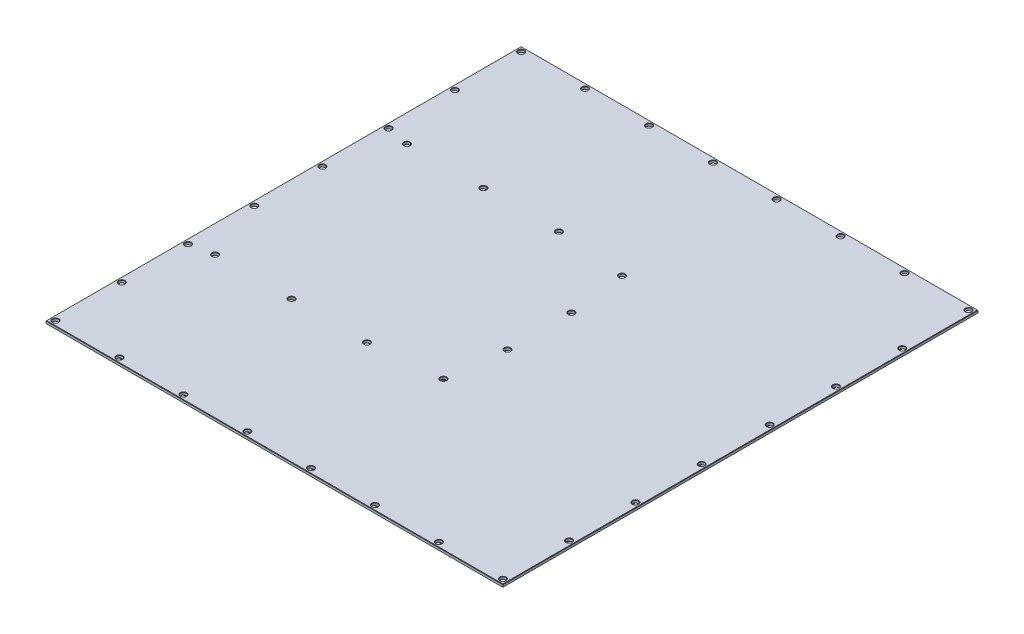
SolidWorks part; units mm, degrees
ref_plane "front" through (0, 0, 0) normal (0, 0, 1) x (1, 0, 0)
ref_plane "top" through (0, 0, 0) normal (0, 1, 0) x (1, 0, 0)
ref_plane "right" through (0, 0, 0) normal (1, 0, 0) x (0, 0, -1)
sketch "Sketch1" plane through (0, 0, 0) normal (0, 1, 0) x (1, 0, 0)
  line L0 (0, 165.1) -> (107.9212, 165.1) construction
  line L1 (0, 330.2) -> (317.5, 330.2)
  line L2 (0, 330.2) -> (0, 0)
  line L3 (0, 0) -> (317.5, 0)
  line L5 (158.75, 0) -> (158.75, 96.4761) construction
  line L6 (317.5, 330.2) -> (317.5, 0)
  circle A0 centre (3.302, 326.898) radius 1.9812
  circle A1 centre (3.302, 141.4526) radius 1.9812
  circle A2 centre (47.752, 326.898) radius 1.9812
  circle A3 centre (92.202, 326.898) radius 1.9812
  circle A4 centre (136.652, 326.898) radius 1.9812
  circle A5 centre (3.302, 280.8478) radius 1.9812
  circle A6 centre (3.302, 234.7976) radius 1.9812
  circle A7 centre (3.302, 188.7474) radius 1.9812
  circle A8 centre (3.302, 95.4024) radius 1.9812
  circle A9 centre (3.302, 49.3522) radius 1.9812
  circle A10 centre (136.652, 3.302) radius 1.9812
  circle A11 centre (92.202, 3.302) radius 1.9812
  circle A12 centre (47.752, 3.302) radius 1.9812
  circle A13 centre (3.302, 3.302) radius 1.9812
  circle A14 centre (314.198, 3.302) radius 1.9812
  circle A15 centre (269.748, 3.302) radius 1.9812
  circle A16 centre (225.298, 3.302) radius 1.9812
  circle A17 centre (180.848, 3.302) radius 1.9812
  circle A18 centre (314.198, 49.3522) radius 1.9812
  circle A19 centre (314.198, 95.4024) radius 1.9812
  circle A20 centre (314.198, 188.7474) radius 1.9812
  circle A21 centre (314.198, 234.7976) radius 1.9812
  circle A22 centre (314.198, 280.8478) radius 1.9812
  circle A23 centre (180.848, 326.898) radius 1.9812
  circle A24 centre (225.298, 326.898) radius 1.9812
  circle A25 centre (269.748, 326.898) radius 1.9812
  circle A26 centre (314.198, 141.4526) radius 1.9812
  circle A27 centre (314.198, 326.898) radius 1.9812
  circle A28 centre (19.05, 231.775) radius 1.9812
  circle A29 centre (72.2122, 231.775) radius 1.9812
  circle A30 centre (124.6378, 231.775) radius 1.9812
  circle A31 centre (177.8, 231.775) radius 1.9812 construction
  circle A32 centre (177.8, 98.425) radius 1.9812 construction
  circle A33 centre (124.6378, 98.425) radius 1.9812
  circle A34 centre (72.2122, 98.425) radius 1.9812
  circle A35 centre (19.05, 98.425) radius 1.9812
  circle A36 centre (177.8, 187.325) radius 1.9812
  circle A37 centre (177.8, 142.875) radius 1.9812
  dimension "D12" = 3.9624
  dimension "D1" = 330.2
  dimension "D2" = 317.5
  dimension "D3" = 44.45
  dimension "D4" = 3.302
  dimension "D5" = 46.0502
  dimension "D6" = 44.196
  dimension "D7" = 47.2948
  dimension "D8" = 3.302
  dimension "D9" = 46.0502
  dimension "D10" = 44.45
  dimension "D11" = 44.45
  dimension "D13" = 19.05
  dimension "D14" = 98.425
  dimension "D15" = 53.1622
  dimension "D16" = 44.45
  dimension "D17" = 177.8
  dimension "D18" = 44.196
  dimension "D19" = 177.8
  dimension "D20" = 52.4256
extrude "Extrude4" add sketch "Sketch1" along normal blind 3.175
sketch "box walls" plane through (0, 0, 0) normal (0, -1, 0) x (1, 0, 0)
  line L0 (0, -165.1) -> (53.4599, -165.1) construction
  line L1 (0, -330.2) -> (0, 0) construction
  line L2 (180.975, -215.9) -> (180.975, -114.3)
  line L3 (295.275, -320.675) -> (22.225, -320.675)
  line L4 (9.525, -307.975) -> (9.525, -247.65)
  line L5 (22.225, -234.95) -> (161.925, -234.95)
  line L6 (307.975, -307.975) -> (307.975, -22.225)
  line L7 (22.225, -95.25) -> (161.925, -95.25)
  line L8 (9.525, -22.225) -> (9.525, -82.55)
  line L9 (295.275, -9.525) -> (22.225, -9.525)
  line L10 (317.5, -330.2) -> (0, -330.2) construction
  line L11 (161.925, -101.6) -> (22.225, -101.6)
  line L12 (174.625, -114.3) -> (174.625, -215.9)
  line L13 (161.925, -228.6) -> (22.225, -228.6)
  line L14 (9.525, -114.3) -> (9.525, -215.9)
  line L15 (317.5, 0) -> (317.5, -330.2) construction
  line L16 (0, 0) -> (317.5, 0) construction
  line L17 (175.3954, -100.8296) -> (170.9053, -105.3197) construction
  line L18 (87.1603, -95.25) -> (87.1603, -101.6) construction
  line L19 (87.1603, -228.6) -> (87.1603, -234.95) construction
  line L20 (180.975, -165.1) -> (174.625, -165.1) construction
  line L21 (0, -330.2) -> (0, 0) construction
  line L22 (0, 0) -> (317.5, 0) construction
  line L23 (0, -330.2) -> (0, 0) construction
  arc A0 (307.975, -307.975) -> (295.275, -320.675) centre (295.275, -307.975) cw
  arc A1 (22.225, -320.675) -> (9.525, -307.975) centre (22.225, -307.975) cw
  arc A2 (9.525, -247.65) -> (22.225, -234.95) centre (22.225, -247.65) cw
  arc A3 (22.225, -228.6) -> (9.525, -215.9) centre (22.225, -215.9) cw
  arc A4 (174.625, -215.9) -> (161.925, -228.6) centre (161.925, -215.9) cw
  arc A5 (161.925, -101.6) -> (174.625, -114.3) centre (161.925, -114.3) cw
  arc A6 (22.225, -101.6) -> (9.525, -114.3) centre (22.225, -114.3) ccw
  arc A7 (161.925, -234.95) -> (180.975, -215.9) centre (161.925, -215.9) ccw
  arc A8 (9.525, -82.55) -> (22.225, -95.25) centre (22.225, -82.55) ccw
  arc A9 (22.225, -9.525) -> (9.525, -22.225) centre (22.225, -22.225) ccw
  arc A10 (307.975, -22.225) -> (295.275, -9.525) centre (295.275, -22.225) ccw
  arc A11 (161.925, -95.25) -> (180.975, -114.3) centre (161.925, -114.3) cw
  circle A12 centre (173.1503, -103.0747) radius 1.9812
  circle A13 centre (173.1503, -227.1253) radius 1.9812
  point P9 (307.975, -165.1)
  point P18 (9.525, -165.1)
  point P43 (180.975, -165.1)
  point P59 (87.1603, -98.425)
  point P60 (87.1603, -231.775)
  point P63 (177.8, -165.1)
  dimension "D1" = 12.7
  dimension "D2" = 19.05
  dimension "D12" = 3.9624
  dimension "D5" = 12.7
  dimension "D13" = 114.3
  dimension "D3" = 6.35
  dimension "3/8 under" = 9.525
  dimension "D4" = 9.525
  dimension "D6" = 139.7
  dimension "D7" = 180.975
  dimension "D8" = 133.35
  dimension "slot width" = 6.35
  dimension "D9" = 177.8
  dimension "D10" = 161.925
  dimension "D11" = 45
  dimension "D14" = 9.525
sketch "Sketch4" plane through (0, 0, 0) normal (0, -1, 0) x (1, 0, 0)
  circle A0 centre (173.1503, -227.1253) radius 1.9812 construction
  circle A1 centre (173.1503, -103.0747) radius 1.9812 construction
  circle A2 centre (173.1503, -227.1253) radius 1.9812
  circle A3 centre (173.1503, -103.0747) radius 1.9812
extrude "new holes" cut sketch "Sketch4" against normal through all
ref_plane "Profile plane" through (9.525, 0, -22.225) normal (0, 0, -1) x (-1, 0, 0)
sketch "groove profile" plane through (9.525, 0, -22.225) normal (0, 0, -1) x (-1, 0, 0)
  line L0 (0.1189, 0) -> (-1.2365, 0)
  line L1 (3.8181, 1.1035) -> (3.8181, 1.397)
  line L2 (9.525, 0) -> (-43.9349, 0) construction
  line L5 (3.8181, 1.397) -> (9.525, 1.397)
  line L6 (0.4145, 1.1035) -> (0.1189, 0)
  line L7 (0.4145, 1.1035) -> (1.8207, 1.1035)
  line L8 (1.8207, 1.1035) -> (2.1163, 0)
  line L9 (2.1163, 0) -> (3.5225, 0)
  line L10 (3.5225, 0) -> (3.8181, 1.1035)
  line L14 (-1.2365, 0) -> (-1.5321, 1.1035)
  line L16 (3.8628, 1.27) -> (3.8181, 1.1035) construction
  line L17 (3.8628, 1.27) -> (5.0058, 1.27) construction
  line L18 (5.0058, 1.27) -> (5.3461, 0) construction
  line L19 (9.525, 0) -> (-307.975, 0) construction
  line L20 (9.525, 0) -> (-307.975, 0) construction
  line L22 (6.4356, 6.0097) -> (6.4356, 1.397) construction
  line L23 (4.4343, 1.27) -> (4.4343, 6.5177) construction
  line L26 (0, -0.9773) -> (0, 6.5177) construction
  line L27 (9.525, 3.175) -> (9.525, 0) construction
  line L28 (2.1163, 0) -> (2.1844, -0.254) construction
  line L29 (2.1844, -0.254) -> (3.4544, -0.254) construction
  line L30 (3.5225, 0) -> (3.4544, -0.254) construction
  line L31 (1.8207, 1.1035) -> (1.7526, 1.3575) construction
  line L32 (0.4145, 1.1035) -> (0.4826, 1.3575) construction
  line L33 (0.4826, 1.3575) -> (1.7526, 1.3575) construction
  line L35 (1.1176, 1.3575) -> (1.1176, 1.8301) construction
  point P3 (1.1176, 1.1035)
  point P17 (2.8194, 0)
  point P25 (-0.5588, 0)
  point P30 (4.4343, 1.27)
  dimension "D2" = 75
  dimension "D3" = 15
  dimension "D4" = 75
  dimension "D5" = 9.525
  dimension "D6" = 1.397
  dimension "D7" = 0.254
  dimension "D8" = 1.27
  dimension "D9" = 75
  dimension "D10" = 1.4061
  dimension "D11" = 0.127
  dimension "D12" = 0.254
  dimension "D13" = 1.27
  dimension "D14" = 75
  dimension "D15" = 1.4061
  dimension "D16" = 1.1035
  dimension "D17" = 6.7056
  dimension "D18" = 8.4074
  dimension "D19" = 10.0838
  dimension "D20" = 1.143
ref_plane "Outside clearance plane" through (3.0894, 1.397, -22.225) normal (0, -1, 0) x (1, 0, 0)
ref_plane "Groove plane" through (8.4074, 1.3575, -22.225) normal (0, 1, 0) x (-1, 0, 0)
ref_plane "Outside chamfer" through (5.0907, 1.27, -22.225) normal (0, 1, 0) x (-1, 0, 0)
sketch "Path centerlines" [suppressed] plane through (8.4963, 0, -22.225) normal (0, 1, 0) x (-1, 0, 0)
  line L0 (0.0965, 0) -> (0.0965, -285.75)
  line L1 (-13.7287, 13.8252) -> (-261.3787, 13.8252)
  line L2 (-13.7287, -302.883) -> (-261.3787, -302.883)
  line L3 (-278.5117, 0) -> (-278.5117, -285.75)
  line L4 (-275.2039, 0) -> (-275.2039, -285.75)
  line L6 (-261.3787, -299.5752) -> (-13.7287, -299.5752)
  line L8 (8.4963, -307.975) -> (8.4963, 22.225) construction
  line L9 (3.4043, 0) -> (3.4043, -285.75)
  line L10 (-13.7287, 17.133) -> (-261.3787, 17.133)
  line L11 (8.4963, 22.225) -> (-283.6037, 22.225) construction
  arc A0 (-13.7287, 13.8252) -> (0.0965, 0) centre (-13.7287, 0) cw
  arc A1 (-1.0287, 0) -> (-13.7287, 12.7) centre (-13.7287, 0) ccw construction
  arc A2 (-275.2039, 0) -> (-261.3787, 13.8252) centre (-261.3787, 0) cw
  arc A3 (-261.3787, 12.7) -> (-274.0787, 0) centre (-261.3787, 0) ccw construction
  arc A4 (-275.2039, -285.75) -> (-261.3787, -299.5752) centre (-261.3787, -285.75) ccw
  arc A5 (-274.0787, -285.75) -> (-261.3787, -298.45) centre (-261.3787, -285.75) ccw construction
  arc A6 (0.0965, -285.75) -> (-13.7287, -299.5752) centre (-13.7287, -285.75) cw
  arc A7 (-13.7287, -298.45) -> (-1.0287, -285.75) centre (-13.7287, -285.75) ccw construction
  arc A8 (-13.7287, 17.133) -> (3.4043, 0) centre (-13.7287, 0) cw
  arc A9 (3.4043, -285.75) -> (-13.7287, -302.883) centre (-13.7287, -285.75) cw
  arc A10 (-261.3787, -302.883) -> (-278.5117, -285.75) centre (-261.3787, -285.75) cw
  arc A11 (-261.3787, 17.133) -> (-278.5117, 0) centre (-261.3787, 0) ccw
  dimension "D6" = 17.133
  dimension "D7" = 13.8252
  dimension "D1" = 3.3078
  dimension "D2" = 5.092
  dimension "D3" = 275.3004
  dimension "D4" = 281.916
  dimension "D5" = 5.092
  dimension "D8" = 3.3078
  dimension "D9" = 320.016
  dimension "D10" = 313.4004
sketch "Sketch7" [suppressed] plane through (8.4455, 1.27, -22.225) normal (0, 1, 0) x (-1, 0, 0)
  line L8 (0.5842, -285.75) -> (0.5842, 0)
  line L9 (-261.4295, -300.1137) -> (-13.7795, -300.1137)
  line L10 (-275.7932, 0) -> (-275.7932, -285.75)
  line L11 (-13.7795, 14.3637) -> (-261.4295, 14.3637)
  line L12 (0.5842, -285.75) -> (0.5842, 0)
  line L13 (-261.4295, -300.1137) -> (-13.7795, -300.1137)
  line L14 (-275.7932, 0) -> (-275.7932, -285.75)
  line L15 (-13.7795, 14.3637) -> (-261.4295, 14.3637)
  line L20 (-13.7795, 13.1953) -> (-261.4295, 13.1953)
  line L21 (-274.6248, 0) -> (-274.6248, -285.75)
  line L22 (-261.4295, -298.9453) -> (-13.7795, -298.9453)
  line L23 (-0.5842, -285.75) -> (-0.5842, 0)
  line L24 (-13.7795, 13.1953) -> (-261.4295, 13.1953)
  line L25 (-274.6248, 0) -> (-274.6248, -285.75)
  line L26 (-261.4295, -298.9453) -> (-13.7795, -298.9453)
  line L27 (-0.5842, -285.75) -> (-0.5842, 0)
  arc A8 (-13.7795, -300.1137) -> (0.5842, -285.75) centre (-13.7795, -285.75) ccw
  arc A9 (-275.7932, -285.75) -> (-261.4295, -300.1137) centre (-261.4295, -285.75) ccw
  arc A10 (-261.4295, 14.3637) -> (-275.7932, 0) centre (-261.4295, 0) ccw
  arc A11 (0.5842, 0) -> (-13.7795, 14.3637) centre (-13.7795, 0) ccw
  arc A12 (-13.7795, -300.1137) -> (0.5842, -285.75) centre (-13.7795, -285.75) ccw
  arc A13 (-275.7932, -285.75) -> (-261.4295, -300.1137) centre (-261.4295, -285.75) ccw
  arc A14 (-261.4295, 14.3637) -> (-275.7932, 0) centre (-261.4295, 0) ccw
  arc A15 (0.5842, 0) -> (-13.7795, 14.3637) centre (-13.7795, 0) ccw
  arc A20 (-261.4295, 13.1953) -> (-274.6248, 0) centre (-261.4295, 0) ccw
  arc A21 (-274.6248, -285.75) -> (-261.4295, -298.9453) centre (-261.4295, -285.75) ccw
  arc A22 (-13.7795, -298.9453) -> (-0.5842, -285.75) centre (-13.7795, -285.75) ccw
  arc A23 (-0.5842, 0) -> (-13.7795, 13.1953) centre (-13.7795, 0) ccw
  arc A24 (-261.4295, 13.1953) -> (-274.6248, 0) centre (-261.4295, 0) ccw
  arc A25 (-274.6248, -285.75) -> (-261.4295, -298.9453) centre (-261.4295, -285.75) ccw
  arc A26 (-13.7795, -298.9453) -> (-0.5842, -285.75) centre (-13.7795, -285.75) ccw
  arc A27 (-0.5842, 0) -> (-13.7795, 13.1953) centre (-13.7795, 0) ccw
  dimension "D1" = 0.5842
  dimension "D2" = 0.5842
extrude "Cut-Extrude1" [suppressed] cut sketch "Sketch7" against normal through all draft 20
sketch "Sketch8" plane through (3.0894, 1.397, -22.225) normal (0, -1, 0) x (1, 0, 0)
  line L0 (2.6175, 0) -> (2.6175, -285.75)
  line L1 (290.4863, 16.5181) -> (19.1356, 16.5181)
  line L2 (290.4863, -302.2681) -> (19.1356, -302.2681)
  line L3 (308.7909, 0) -> (308.7909, -285.75)
  line L5 (-24.3383, 36.2782) -> (311.3325, 36.2782)
  line L6 (-24.3383, 36.2782) -> (-24.3383, -328.6533)
  line L7 (-24.3383, -328.6533) -> (311.3325, -328.6533)
  line L8 (311.3325, 36.2782) -> (311.3325, -328.6533)
  arc A0 (19.1356, 16.5181) -> (2.6175, 0) centre (19.1356, 0) ccw
  arc A1 (19.1356, 12.7) -> (6.4356, 0) centre (19.1356, 0) ccw construction
  arc A2 (2.6175, -285.75) -> (19.1356, -302.2681) centre (19.1356, -285.75) ccw
  arc A3 (6.4356, -285.75) -> (19.1356, -298.45) centre (19.1356, -285.75) ccw construction
  arc A4 (308.7909, 0) -> (290.4863, 16.5181) centre (292.1856, 0) ccw
  arc A7 (304.8856, 0) -> (292.1856, 12.7) centre (292.1856, 0) ccw construction
  arc A8 (308.7909, -285.75) -> (290.4863, -302.2681) centre (292.1856, -285.75) cw
  arc A9 (292.1856, -298.45) -> (304.8856, -285.75) centre (292.1856, -285.75) ccw construction
extrude "Cut-Extrude2" [suppressed] cut sketch "Sketch8" along normal through all
sketch "Sketch10" [suppressed] plane through (5.092, 1.27, -22.225) normal (0, 1, 0) x (-1, 0, 0)
  line L8 (0.508, -285.75) -> (0.508, 0)
  line L9 (-264.783, -303.391) -> (-17.133, -303.391)
  line L10 (-282.424, 0) -> (-282.424, -285.75)
  line L11 (-17.133, 17.641) -> (-264.783, 17.641)
  line L12 (0.508, -285.75) -> (0.508, 0)
  line L13 (-264.783, -303.391) -> (-17.133, -303.391)
  line L14 (-282.424, 0) -> (-282.424, -285.75)
  line L15 (-17.133, 17.641) -> (-264.783, 17.641)
  line L20 (-0.508, -285.75) -> (-0.508, 0)
  line L21 (-264.783, -302.375) -> (-17.133, -302.375)
  line L22 (-281.408, 0) -> (-281.408, -285.75)
  line L23 (-17.133, 16.625) -> (-264.783, 16.625)
  line L24 (-0.508, -285.75) -> (-0.508, 0)
  line L25 (-264.783, -302.375) -> (-17.133, -302.375)
  line L26 (-281.408, 0) -> (-281.408, -285.75)
  line L27 (-17.133, 16.625) -> (-264.783, 16.625)
  arc A8 (-17.133, -303.391) -> (0.508, -285.75) centre (-17.133, -285.75) ccw
  arc A9 (-282.424, -285.75) -> (-264.783, -303.391) centre (-264.783, -285.75) ccw
  arc A10 (-264.783, 17.641) -> (-282.424, 0) centre (-264.783, 0) ccw
  arc A11 (0.508, 0) -> (-17.133, 17.641) centre (-17.133, 0) ccw
  arc A12 (-17.133, -303.391) -> (0.508, -285.75) centre (-17.133, -285.75) ccw
  arc A13 (-282.424, -285.75) -> (-264.783, -303.391) centre (-264.783, -285.75) ccw
  arc A14 (-264.783, 17.641) -> (-282.424, 0) centre (-264.783, 0) ccw
  arc A15 (0.508, 0) -> (-17.133, 17.641) centre (-17.133, 0) ccw
  arc A20 (-17.133, -302.375) -> (-0.508, -285.75) centre (-17.133, -285.75) ccw
  arc A21 (-281.408, -285.75) -> (-264.783, -302.375) centre (-264.783, -285.75) ccw
  arc A22 (-264.783, 16.625) -> (-281.408, 0) centre (-264.783, 0) ccw
  arc A23 (-0.508, 0) -> (-17.133, 16.625) centre (-17.133, 0) ccw
  arc A24 (-17.133, -302.375) -> (-0.508, -285.75) centre (-17.133, -285.75) ccw
  arc A25 (-281.408, -285.75) -> (-264.783, -302.375) centre (-264.783, -285.75) ccw
  arc A26 (-264.783, 16.625) -> (-281.408, 0) centre (-264.783, 0) ccw
  arc A27 (-0.508, 0) -> (-17.133, 16.625) centre (-17.133, 0) ccw
  dimension "D1" = 0.508
  dimension "D2" = 0.508
extrude "Cut-Extrude3" [suppressed] cut sketch "Sketch10" against normal through all draft 20
sketch "Sketch11" plane through (0, 0, 0) normal (0, -1, 0) x (1, 0, 0)
  line L0 (0, -165.1) -> (-57.7632, -165.1) construction
  line L1 (6.7005, -307.975) -> (6.7005, -22.225)
  line L2 (22.225, -6.7005) -> (295.2648, -6.7005)
  line L3 (310.7893, -22.225) -> (310.7893, -307.975)
  line L4 (10.0813, -22.225) -> (10.0813, -82.55)
  line L5 (22.225, -94.6937) -> (161.925, -94.6937)
  line L6 (181.5313, -114.3) -> (181.5313, -215.9)
  line L7 (22.225, -10.0813) -> (295.2648, -10.0813)
  line L8 (307.4086, -22.225) -> (307.4086, -307.975)
  line L9 (10.0813, -114.3) -> (10.0813, -215.9)
  line L10 (22.225, -102.1563) -> (161.925, -102.1563)
  line L11 (174.0687, -114.3) -> (174.0687, -215.9)
  line L12 (0, -330.2) -> (0, 0) construction
  line L13 (22.225, -228.0437) -> (161.925, -228.0437)
  line L14 (22.225, -320.1187) -> (295.2648, -320.1187)
  line L15 (22.225, -235.5063) -> (161.925, -235.5063)
  line L16 (10.0813, -307.975) -> (10.0813, -247.65)
  line L17 (22.225, -323.4995) -> (295.2648, -323.4995)
  line L18 (317.5, -330.2) -> (0, -330.2) construction
  line L19 (312.3991, -22.225) -> (312.3991, -307.975)
  line L20 (5.0907, -22.225) -> (5.0907, -307.975)
  line L21 (22.225, -5.0907) -> (295.2648, -5.0907)
  line L22 (22.225, -325.1093) -> (295.2648, -325.1093)
  line L23 (8.4074, -22.225) -> (8.4074, -307.975)
  line L24 (22.225, -8.4074) -> (295.2648, -8.4074)
  line L25 (22.225, -321.7926) -> (295.2648, -321.7926)
  line L26 (309.0824, -22.225) -> (309.0824, -307.975)
  line L27 (0, 0) -> (317.5, 0) construction
  arc A0 (295.2648, -6.7005) -> (310.7893, -22.225) centre (295.2648, -22.225) cw
  arc A1 (6.7005, -22.225) -> (22.225, -6.7005) centre (22.225, -22.225) cw
  arc A2 (22.225, -323.4995) -> (6.7005, -307.975) centre (22.225, -307.975) cw
  arc A3 (295.2648, -323.4995) -> (310.7893, -307.975) centre (295.2648, -307.975) ccw
  arc A4 (10.0813, -22.225) -> (22.225, -10.0813) centre (22.225, -22.225) cw
  arc A5 (295.2648, -10.0813) -> (307.4086, -22.225) centre (295.2648, -22.225) cw
  arc A6 (295.2648, -320.1187) -> (307.4086, -307.975) centre (295.2648, -307.975) ccw
  arc A7 (22.225, -320.1187) -> (10.0813, -307.975) centre (22.225, -307.975) cw
  arc A8 (22.225, -235.5063) -> (10.0813, -247.65) centre (22.225, -247.65) ccw
  arc A9 (10.0813, -82.55) -> (22.225, -94.6937) centre (22.225, -82.55) ccw
  arc A10 (161.925, -228.0437) -> (174.0687, -215.9) centre (161.925, -215.9) ccw
  arc A11 (161.925, -102.1563) -> (174.0687, -114.3) centre (161.925, -114.3) cw
  arc A12 (10.0813, -114.3) -> (22.225, -102.1563) centre (22.225, -114.3) cw
  arc A13 (22.225, -228.0437) -> (10.0813, -215.9) centre (22.225, -215.9) cw
  arc A14 (161.925, -235.5063) -> (181.5313, -215.9) centre (161.925, -215.9) ccw
  arc A15 (161.925, -94.6937) -> (181.5313, -114.3) centre (161.925, -114.3) cw
  arc A16 (22.225, -5.0907) -> (5.0907, -22.225) centre (22.225, -22.225) ccw
  arc A17 (295.2648, -5.0907) -> (312.3991, -22.225) centre (295.2648, -22.225) cw
  arc A18 (5.0907, -307.975) -> (22.225, -325.1093) centre (22.225, -307.975) ccw
  arc A19 (312.3991, -307.975) -> (295.2648, -325.1093) centre (295.2648, -307.975) cw
  arc A20 (22.225, -8.4074) -> (8.4074, -22.225) centre (22.225, -22.225) ccw
  arc A21 (8.4074, -307.975) -> (22.225, -321.7926) centre (22.225, -307.975) ccw
  arc A22 (295.2648, -321.7926) -> (309.0824, -307.975) centre (295.2648, -307.975) ccw
  arc A23 (295.2648, -8.4074) -> (309.0824, -22.225) centre (295.2648, -22.225) cw
  point P19 (174.0687, -165.1)
  point P20 (10.0813, -165.1)
  point P21 (307.4086, -165.1)
  point P23 (181.5313, -165.1)
  point P25 (310.7893, -165.1)
  point P26 (6.7005, -165.1)
  point P28 (310.7893, -6.7005)
  point P31 (6.7005, -6.7005)
  point P34 (6.7005, -323.4995)
  point P37 (310.7893, -323.4995)
  point P40 (10.0813, -10.0813)
  point P43 (307.4086, -10.0813)
  point P46 (307.4086, -320.1187)
  point P49 (10.0813, -320.1187)
  point P52 (10.0813, -235.5063)
  point P55 (10.0813, -94.6937)
  point P58 (174.0687, -228.0437)
  point P61 (174.0687, -102.1563)
  point P64 (10.0813, -102.1563)
  point P67 (10.0813, -228.0437)
  point P70 (181.5313, -235.5063)
  point P73 (181.5313, -94.6937)
  dimension "D1" = 15.5245
  dimension "D2" = 12.1437
  dimension "D3" = 19.6063
  dimension "D19" = 13.8176
  dimension "D4" = 3.3807
  dimension "D5" = 6.7005
  dimension "D6" = 6.7005
  dimension "D7" = 3.3807
  dimension "D8" = 3.3807
  dimension "D9" = 304.0888
  dimension "D10" = 316.799
  dimension "D11" = 140.8125
  dimension "D12" = 7.4625
  dimension "D13" = 7.4625
  dimension "D14" = 84.6125
  dimension "D15" = 174.8307
  dimension "D16" = 125.8875
  dimension "D17" = 310.0375
  dimension "D18" = 297.3273
  dimension "D20" = 8.4074
  dimension "D21" = 8.4074
  dimension "D22" = 300.675
  dimension "D23" = 313.3852
sketch "Sketch12" plane through (3.0894, 1.397, -22.225) normal (0, -1, 0) x (1, 0, 0)
  line L0 (2.6175, 0) -> (2.6175, -285.75)
  line L1 (19.1356, 16.5181) -> (292.1755, 16.5181)
  line L2 (-3.0894, -142.875) -> (-60.8526, -142.875) construction
  line L3 (-3.0894, -142.875) -> (-60.8526, -142.875) construction
  line L4 (308.6936, 0) -> (308.6936, -285.75)
  line L5 (19.1356, -302.2681) -> (292.1755, -302.2681)
  line L7 (-29.7348, 54.4125) -> (335.2944, 54.4125)
  line L8 (-29.7348, 54.4125) -> (-29.7348, -333.3982)
  line L9 (-29.7348, -333.3982) -> (335.2944, -333.3982)
  line L10 (335.2944, 54.4125) -> (335.2944, -333.3982)
  arc A0 (2.6175, 0) -> (19.1356, 16.5181) centre (19.1356, 0) cw
  arc A1 (19.1356, 15.5245) -> (3.6111, 0) centre (19.1356, 0) ccw construction
  arc A2 (292.1755, 16.5181) -> (308.6936, 0) centre (292.1755, 0) cw
  arc A3 (307.6999, 0) -> (292.1755, 15.5245) centre (292.1755, 0) ccw construction
  arc A4 (292.1755, -302.2681) -> (308.6936, -285.75) centre (292.1755, -285.75) ccw
  arc A5 (2.6175, -285.75) -> (19.1356, -302.2681) centre (19.1356, -285.75) ccw
  point P12 (2.6175, -142.875)
  point P23 (308.6936, -142.875)
extrude "Cut-Extrude4" cut sketch "Sketch12" along normal through all
sketch "Sketch14" plane through (5.0907, 1.27, -22.225) normal (0, 1, 0) x (-1, 0, 0)
  line L8 (-0.5715, -285.75) -> (-0.5715, 0)
  line L9 (-290.1741, -302.3128) -> (-17.1343, -302.3128)
  line L10 (-306.7368, 0) -> (-306.7368, -285.75)
  line L11 (-17.1343, 16.5628) -> (-290.1741, 16.5628)
  line L12 (-0.5715, -285.75) -> (-0.5715, 0)
  line L13 (-290.1741, -302.3128) -> (-17.1343, -302.3128)
  line L14 (-306.7368, 0) -> (-306.7368, -285.75)
  line L15 (-17.1343, 16.5628) -> (-290.1741, 16.5628)
  line L20 (0.5715, -285.75) -> (0.5715, 0)
  line L21 (-290.1741, -303.4558) -> (-17.1343, -303.4558)
  line L22 (-307.8798, 0) -> (-307.8798, -285.75)
  line L23 (-17.1343, 17.7058) -> (-290.1741, 17.7058)
  line L24 (0.5715, -285.75) -> (0.5715, 0)
  line L25 (-290.1741, -303.4558) -> (-17.1343, -303.4558)
  line L26 (-307.8798, 0) -> (-307.8798, -285.75)
  line L27 (-17.1343, 17.7058) -> (-290.1741, 17.7058)
  arc A8 (-17.1343, -302.3128) -> (-0.5715, -285.75) centre (-17.1343, -285.75) ccw
  arc A9 (-306.7368, -285.75) -> (-290.1741, -302.3128) centre (-290.1741, -285.75) ccw
  arc A10 (-290.1741, 16.5628) -> (-306.7368, 0) centre (-290.1741, 0) ccw
  arc A11 (-0.5715, 0) -> (-17.1343, 16.5628) centre (-17.1343, 0) ccw
  arc A12 (-17.1343, -302.3128) -> (-0.5715, -285.75) centre (-17.1343, -285.75) ccw
  arc A13 (-306.7368, -285.75) -> (-290.1741, -302.3128) centre (-290.1741, -285.75) ccw
  arc A14 (-290.1741, 16.5628) -> (-306.7368, 0) centre (-290.1741, 0) ccw
  arc A15 (-0.5715, 0) -> (-17.1343, 16.5628) centre (-17.1343, 0) ccw
  arc A20 (-17.1343, -303.4558) -> (0.5715, -285.75) centre (-17.1343, -285.75) ccw
  arc A21 (-307.8798, -285.75) -> (-290.1741, -303.4558) centre (-290.1741, -285.75) ccw
  arc A22 (-290.1741, 17.7058) -> (-307.8798, 0) centre (-290.1741, 0) ccw
  arc A23 (0.5715, 0) -> (-17.1343, 17.7058) centre (-17.1343, 0) ccw
  arc A24 (-17.1343, -303.4558) -> (0.5715, -285.75) centre (-17.1343, -285.75) ccw
  arc A25 (-307.8798, -285.75) -> (-290.1741, -303.4558) centre (-290.1741, -285.75) ccw
  arc A26 (-290.1741, 17.7058) -> (-307.8798, 0) centre (-290.1741, 0) ccw
  arc A27 (0.5715, 0) -> (-17.1343, 17.7058) centre (-17.1343, 0) ccw
  dimension "D1" = 0.5715
  dimension "D2" = 0.5715
extrude "Cut-Extrude5" cut sketch "Sketch14" against normal through all draft 15 draft outward yes
sketch "Sketch15" plane through (8.4074, 1.3575, -22.225) normal (0, 1, 0) x (-1, 0, 0)
  line L0 (0, 0) -> (0, -285.75) construction
  line L40 (-13.8176, -78.8899) -> (-153.5176, -78.8899)
  line L41 (-166.7027, -92.075) -> (-166.7027, -193.675)
  line L42 (-153.5176, -206.8601) -> (-13.8176, -206.8601)
  line L43 (-0.6325, -193.675) -> (-0.6325, -92.075)
  line L44 (-13.8176, -78.8899) -> (-153.5176, -78.8899)
  line L45 (-166.7027, -92.075) -> (-166.7027, -193.675)
  line L46 (-153.5176, -206.8601) -> (-13.8176, -206.8601)
  line L47 (-0.6325, -193.675) -> (-0.6325, -92.075)
  line L54 (-13.8176, -212.2399) -> (-153.5176, -212.2399)
  line L55 (-172.0825, -193.675) -> (-172.0825, -92.075)
  line L56 (0.635, -285.75) -> (0.635, 0)
  line L57 (-286.8574, -300.2026) -> (-13.8176, -300.2026)
  line L58 (-301.31, 0) -> (-301.31, -285.75)
  line L59 (-13.8176, 14.4526) -> (-286.8574, 14.4526)
  line L60 (0.635, -285.75) -> (0.635, 0)
  line L61 (-286.8574, -300.2026) -> (-13.8176, -300.2026)
  line L62 (-301.31, 0) -> (-301.31, -285.75)
  line L63 (-13.8176, 14.4526) -> (-286.8574, 14.4526)
  line L64 (-153.5176, -73.5101) -> (-13.8176, -73.5101)
  line L65 (-0.6325, -60.325) -> (-0.6325, 0)
  line L66 (-13.8176, 13.1851) -> (-286.8574, 13.1851)
  line L67 (-300.0426, 0) -> (-300.0426, -285.75)
  line L68 (-286.8574, -298.9351) -> (-13.8176, -298.9351)
  line L69 (-0.6325, -285.75) -> (-0.6325, -225.425)
  line L70 (-13.8176, -212.2399) -> (-153.5176, -212.2399)
  line L71 (-172.0825, -193.675) -> (-172.0825, -92.075)
  line L72 (-153.5176, -73.5101) -> (-13.8176, -73.5101)
  line L73 (-0.6325, -60.325) -> (-0.6325, 0)
  line L74 (-13.8176, 13.1851) -> (-286.8574, 13.1851)
  line L75 (-300.0426, 0) -> (-300.0426, -285.75)
  line L76 (-286.8574, -298.9351) -> (-13.8176, -298.9351)
  line L77 (-0.6325, -285.75) -> (-0.6325, -225.425)
  arc A40 (-153.5176, -78.8899) -> (-166.7027, -92.075) centre (-153.5176, -92.075) ccw
  arc A41 (-166.7027, -193.675) -> (-153.5176, -206.8601) centre (-153.5176, -193.675) ccw
  arc A42 (-13.8176, -206.8601) -> (-0.6325, -193.675) centre (-13.8176, -193.675) ccw
  arc A43 (-0.6325, -92.075) -> (-13.8176, -78.8899) centre (-13.8176, -92.075) ccw
  arc A44 (-153.5176, -78.8899) -> (-166.7027, -92.075) centre (-153.5176, -92.075) ccw
  arc A45 (-166.7027, -193.675) -> (-153.5176, -206.8601) centre (-153.5176, -193.675) ccw
  arc A46 (-13.8176, -206.8601) -> (-0.6325, -193.675) centre (-13.8176, -193.675) ccw
  arc A47 (-0.6325, -92.075) -> (-13.8176, -78.8899) centre (-13.8176, -92.075) ccw
  arc A52 (-172.0825, -193.675) -> (-153.5176, -212.2399) centre (-153.5176, -193.675) ccw
  arc A53 (-153.5176, -73.5101) -> (-172.0825, -92.075) centre (-153.5176, -92.075) ccw
  arc A54 (-13.8176, -73.5101) -> (-0.6325, -60.325) centre (-13.8176, -60.325) ccw
  arc A55 (-0.6325, 0) -> (-13.8176, 13.1851) centre (-13.8176, 0) ccw
  arc A56 (-13.8176, -300.2026) -> (0.635, -285.75) centre (-13.8176, -285.75) ccw
  arc A57 (-301.31, -285.75) -> (-286.8574, -300.2026) centre (-286.8574, -285.75) ccw
  arc A58 (-286.8574, 14.4526) -> (-301.31, 0) centre (-286.8574, 0) ccw
  arc A59 (0.635, 0) -> (-13.8176, 14.4526) centre (-13.8176, 0) ccw
  arc A60 (-13.8176, -300.2026) -> (0.635, -285.75) centre (-13.8176, -285.75) ccw
  arc A61 (-301.31, -285.75) -> (-286.8574, -300.2026) centre (-286.8574, -285.75) ccw
  arc A62 (-286.8574, 14.4526) -> (-301.31, 0) centre (-286.8574, 0) ccw
  arc A63 (0.635, 0) -> (-13.8176, 14.4526) centre (-13.8176, 0) ccw
  arc A64 (-286.8574, 13.1851) -> (-300.0426, 0) centre (-286.8574, 0) ccw
  arc A65 (-300.0426, -285.75) -> (-286.8574, -298.9351) centre (-286.8574, -285.75) ccw
  arc A66 (-13.8176, -298.9351) -> (-0.6325, -285.75) centre (-13.8176, -285.75) ccw
  arc A67 (-0.6325, -225.425) -> (-13.8176, -212.2399) centre (-13.8176, -225.425) ccw
  arc A68 (-172.0825, -193.675) -> (-153.5176, -212.2399) centre (-153.5176, -193.675) ccw
  arc A69 (-153.5176, -73.5101) -> (-172.0825, -92.075) centre (-153.5176, -92.075) ccw
  arc A70 (-13.8176, -73.5101) -> (-0.6325, -60.325) centre (-13.8176, -60.325) ccw
  arc A71 (-0.6325, 0) -> (-13.8176, 13.1851) centre (-13.8176, 0) ccw
  arc A72 (-286.8574, 13.1851) -> (-300.0426, 0) centre (-286.8574, 0) ccw
  arc A73 (-300.0426, -285.75) -> (-286.8574, -298.9351) centre (-286.8574, -285.75) ccw
  arc A74 (-13.8176, -298.9351) -> (-0.6325, -285.75) centre (-13.8176, -285.75) ccw
  arc A75 (-0.6325, -225.425) -> (-13.8176, -212.2399) centre (-13.8176, -225.425) ccw
  dimension "D4" = 0.6325
  dimension "D1" = 1.0414
  dimension "D2" = 1.0414
  dimension "D3" = 0.635
extrude "Cut-Extrude6" cut sketch "Sketch15" against normal through all draft 15 draft outward yes
sketch "Sketch16" plane through (0, 1.3575, 0) normal (0, -1, 0) x (1, 0, 0)
  line L0 (9.0399, -247.65) -> (7.7724, -247.65)
  line L1 (7.7724, -307.975) -> (7.7724, -22.225) construction
  line L2 (7.7724, -247.65) -> (7.7724, -215.9)
  line L3 (9.0399, -215.9) -> (7.7724, -215.9)
  line L4 (22.225, -229.0851) -> (22.225, -234.4649)
  arc A0 (9.0399, -215.9) -> (22.225, -229.0851) centre (22.225, -215.9) ccw construction
  arc A1 (22.225, -234.4649) -> (9.0399, -247.65) centre (22.225, -247.65) ccw construction
  arc A2 (9.0399, -215.9) -> (22.225, -229.0851) centre (22.225, -215.9) ccw
  arc A3 (22.225, -234.4649) -> (9.0399, -247.65) centre (22.225, -247.65) ccw
sketch "Sketch17" plane through (0, 1.3575, 0) normal (0, -1, 0) x (1, 0, 0)
  line L0 (22.225, -101.1149) -> (22.225, -95.7351)
  line L1 (9.0399, -114.3) -> (7.7724, -114.3)
  line L2 (7.7724, -307.975) -> (7.7724, -22.225) construction
  line L3 (7.7724, -114.3) -> (7.7724, -82.55)
  line L4 (7.7724, -82.55) -> (9.0399, -82.55)
  arc A0 (22.225, -101.1149) -> (9.0399, -114.3) centre (22.225, -114.3) ccw construction
  arc A1 (9.0399, -82.55) -> (22.225, -95.7351) centre (22.225, -82.55) ccw construction
  arc A2 (22.225, -101.1149) -> (9.0399, -114.3) centre (22.225, -114.3) ccw
  arc A3 (9.0399, -82.55) -> (22.225, -95.7351) centre (22.225, -82.55) ccw
sketch "Sketch18" plane through (0, 1.3575, 0) normal (0, -1, 0) x (1, 0, 0)
  line L0 (-75.7061, -165.1) -> (0, -165.1) construction
  line L2 (0, 0) -> (0, -330.2) construction
  line L4 (78.8035, -217.4748) -> (118.0465, -217.4748) construction
  line L5 (78.8035, -217.4748) -> (78.8035, -246.0752) construction
  line L6 (78.8035, -246.0752) -> (118.0465, -246.0752) construction
  line L7 (118.0465, -217.4748) -> (118.0465, -246.0752) construction
  line L8 (80.0735, -216.9668) -> (116.7765, -216.9668)
  line L9 (118.5545, -218.7448) -> (118.5545, -244.8052)
  line L10 (80.0735, -246.5832) -> (116.7765, -246.5832)
  line L11 (78.2955, -218.7448) -> (78.2955, -244.8052)
  line L12 (78.2955, -111.4552) -> (78.2955, -85.3948)
  line L13 (80.0735, -83.6168) -> (116.7765, -83.6168)
  line L14 (118.5545, -111.4552) -> (118.5545, -85.3948)
  line L15 (80.0735, -113.2332) -> (116.7765, -113.2332)
  circle A0 centre (72.2122, -231.775) radius 1.9812 construction
  arc A1 (80.0735, -216.9668) -> (78.2955, -218.7448) centre (80.0735, -218.7448) ccw
  arc A2 (116.7765, -216.9668) -> (118.5545, -218.7448) centre (116.7765, -218.7448) cw
  arc A3 (118.5545, -244.8052) -> (116.7765, -246.5832) centre (116.7765, -244.8052) cw
  arc A4 (80.0735, -246.5832) -> (78.2955, -244.8052) centre (80.0735, -244.8052) cw
  arc A5 (80.0735, -83.6168) -> (78.2955, -85.3948) centre (80.0735, -85.3948) ccw
  arc A6 (118.5545, -85.3948) -> (116.7765, -83.6168) centre (116.7765, -85.3948) ccw
  arc A7 (116.7765, -113.2332) -> (118.5545, -111.4552) centre (116.7765, -111.4552) ccw
  arc A8 (80.0735, -113.2332) -> (78.2955, -111.4552) centre (80.0735, -111.4552) cw
  circle A9 centre (72.2122, -231.775) radius 1.9812 construction
  point P10 (98.425, -246.0752)
  point P36 (78.8035, -231.775)
  dimension "D6" = 1.778
  dimension "D3" = 4.1021
  dimension "D1" = 39.243
  dimension "D2" = 28.6004
  dimension "D4" = 98.425
  dimension "D7" = 29.6164
  dimension "D8" = 40.259
  dimension "D5" = 0.508
extrude "Cut-Extrude7" cut sketch "Sketch18" along normal through all
sketch "Sketch19" plane through (0, 1.3575, 0) normal (0, -1, 0) x (1, 0, 0)
  line L0 (78.2955, -234.4649) -> (78.2955, -244.8052) construction
  line L1 (78.2955, -218.7448) -> (78.2955, -229.0851) construction
  line L2 (116.7765, -216.9668) -> (80.0735, -216.9668) construction
  line L3 (80.0735, -246.5832) -> (116.7765, -246.5832) construction
  line L4 (118.5545, -244.8052) -> (118.5545, -234.4649) construction
  line L5 (118.5545, -229.0851) -> (118.5545, -218.7448) construction
  line L6 (78.2955, -234.4649) -> (78.2955, -244.8052)
  line L7 (78.2955, -218.7448) -> (78.2955, -229.0851)
  line L8 (116.7765, -216.9668) -> (80.0735, -216.9668)
  line L9 (80.0735, -246.5832) -> (116.7765, -246.5832)
  line L10 (118.5545, -244.8052) -> (118.5545, -234.4649)
  line L11 (118.5545, -229.0851) -> (118.5545, -218.7448)
  line L12 (78.2955, -234.4649) -> (78.2955, -229.0851)
  line L13 (118.5545, -234.4649) -> (118.5545, -229.0851)
  arc A0 (78.2955, -244.8052) -> (80.0735, -246.5832) centre (80.0735, -244.8052) ccw construction
  arc A1 (80.0735, -216.9668) -> (78.2955, -218.7448) centre (80.0735, -218.7448) ccw construction
  arc A2 (118.5545, -218.7448) -> (116.7765, -216.9668) centre (116.7765, -218.7448) ccw construction
  arc A3 (116.7765, -246.5832) -> (118.5545, -244.8052) centre (116.7765, -244.8052) ccw construction
  arc A4 (78.2955, -244.8052) -> (80.0735, -246.5832) centre (80.0735, -244.8052) ccw
  arc A5 (80.0735, -216.9668) -> (78.2955, -218.7448) centre (80.0735, -218.7448) ccw
  arc A6 (118.5545, -218.7448) -> (116.7765, -216.9668) centre (116.7765, -218.7448) ccw
  arc A7 (116.7765, -246.5832) -> (118.5545, -244.8052) centre (116.7765, -244.8052) ccw
sketch "Sketch20" plane through (0, 1.3575, 0) normal (0, -1, 0) x (1, 0, 0)
  line L0 (118.5545, -95.7351) -> (118.5545, -85.3948) construction
  line L1 (116.7765, -83.6168) -> (80.0735, -83.6168) construction
  line L2 (78.2955, -85.3948) -> (78.2955, -95.7351) construction
  line L3 (78.2955, -101.1149) -> (78.2955, -111.4552) construction
  line L4 (22.225, -322.4276) -> (295.2648, -322.4276)
  line L5 (309.7174, -307.975) -> (309.7174, -22.225)
  line L6 (295.2648, -7.7724) -> (22.225, -7.7724)
  line L7 (7.7724, -22.225) -> (7.7724, -307.975)
  line L8 (22.225, -322.4276) -> (295.2648, -322.4276)
  line L9 (309.7174, -307.975) -> (309.7174, -22.225)
  line L10 (295.2648, -7.7724) -> (22.225, -7.7724)
  line L11 (7.7724, -22.225) -> (7.7724, -307.975)
  line L12 (80.0735, -113.2332) -> (116.7765, -113.2332) construction
  line L13 (118.5545, -111.4552) -> (118.5545, -101.1149) construction
  line L14 (118.5545, -95.7351) -> (118.5545, -85.3948)
  line L15 (116.7765, -83.6168) -> (80.0735, -83.6168)
  line L16 (78.2955, -85.3948) -> (78.2955, -95.7351)
  line L17 (78.2955, -101.1149) -> (78.2955, -111.4552)
  line L18 (80.0735, -113.2332) -> (116.7765, -113.2332)
  line L19 (118.5545, -111.4552) -> (118.5545, -101.1149)
  line L20 (118.5545, -101.1149) -> (118.5545, -95.7351)
  line L21 (78.2955, -101.1149) -> (78.2955, -95.7351)
  arc A0 (118.5545, -85.3948) -> (116.7765, -83.6168) centre (116.7765, -85.3948) ccw construction
  arc A1 (80.0735, -83.6168) -> (78.2955, -85.3948) centre (80.0735, -85.3948) ccw construction
  arc A2 (78.2955, -111.4552) -> (80.0735, -113.2332) centre (80.0735, -111.4552) ccw construction
  arc A3 (116.7765, -113.2332) -> (118.5545, -111.4552) centre (116.7765, -111.4552) ccw construction
  arc A4 (7.7724, -307.975) -> (22.225, -322.4276) centre (22.225, -307.975) ccw
  arc A5 (295.2648, -322.4276) -> (309.7174, -307.975) centre (295.2648, -307.975) ccw
  arc A6 (309.7174, -22.225) -> (295.2648, -7.7724) centre (295.2648, -22.225) ccw
  arc A7 (22.225, -7.7724) -> (7.7724, -22.225) centre (22.225, -22.225) ccw
  arc A8 (7.7724, -307.975) -> (22.225, -322.4276) centre (22.225, -307.975) ccw
  arc A9 (295.2648, -322.4276) -> (309.7174, -307.975) centre (295.2648, -307.975) ccw
  arc A10 (309.7174, -22.225) -> (295.2648, -7.7724) centre (295.2648, -22.225) ccw
  arc A11 (22.225, -7.7724) -> (7.7724, -22.225) centre (22.225, -22.225) ccw
  arc A12 (118.5545, -85.3948) -> (116.7765, -83.6168) centre (116.7765, -85.3948) ccw
  arc A13 (80.0735, -83.6168) -> (78.2955, -85.3948) centre (80.0735, -85.3948) ccw
  arc A14 (78.2955, -111.4552) -> (80.0735, -113.2332) centre (80.0735, -111.4552) ccw
  arc A15 (116.7765, -113.2332) -> (118.5545, -111.4552) centre (116.7765, -111.4552) ccw
  dimension "D1" = 0
sketch "Sketch22" plane through (0, 1.3575, 0) normal (0, -1, 0) x (1, 0, 0)
  line L0 (118.5545, -101.1149) -> (78.2955, -101.1149)
  line L1 (118.5545, -229.0851) -> (78.2955, -229.0851)
  line L2 (22.225, -101.1149) -> (78.2955, -101.1149) construction
  line L3 (118.5545, -101.1149) -> (161.925, -101.1149) construction
  line L4 (175.1101, -114.3) -> (175.1101, -215.9) construction
  line L5 (161.925, -229.0851) -> (118.5545, -229.0851) construction
  line L6 (78.2955, -229.0851) -> (22.225, -229.0851) construction
  line L7 (22.225, -101.1149) -> (78.2955, -101.1149)
  line L8 (118.5545, -101.1149) -> (161.925, -101.1149)
  line L9 (175.1101, -114.3) -> (175.1101, -215.9)
  line L10 (161.925, -229.0851) -> (118.5545, -229.0851)
  line L11 (78.2955, -229.0851) -> (22.225, -229.0851)
  arc A0 (175.1101, -114.3) -> (161.925, -101.1149) centre (161.925, -114.3) ccw construction
  arc A1 (161.925, -229.0851) -> (175.1101, -215.9) centre (161.925, -215.9) ccw construction
  arc A2 (175.1101, -114.3) -> (161.925, -101.1149) centre (161.925, -114.3) ccw
  arc A3 (161.925, -229.0851) -> (175.1101, -215.9) centre (161.925, -215.9) ccw
  arc A4 (22.225, -101.1149) -> (9.0399, -114.3) centre (22.225, -114.3) ccw construction
  arc A5 (9.0399, -215.9) -> (22.225, -229.0851) centre (22.225, -215.9) ccw construction
  arc A6 (22.225, -101.1149) -> (9.0399, -114.3) centre (22.225, -114.3) ccw
  arc A7 (9.0399, -215.9) -> (22.225, -229.0851) centre (22.225, -215.9) ccw
sketch "Sketch23" plane through (0, 1.3575, 0) normal (0, -1, 0) x (1, 0, 0)
  line L2 (78.2955, -98.425) -> (22.225, -98.425)
  line L3 (78.2955, -98.425) -> (22.225, -98.425)
  line L5 (161.925, -98.425) -> (118.5545, -98.425)
  line L6 (161.925, -98.425) -> (118.5545, -98.425)
  line L8 (177.8, -215.9) -> (177.8, -114.3)
  line L9 (177.8, -215.9) -> (177.8, -114.3)
  line L11 (118.5545, -231.775) -> (161.925, -231.775)
  line L12 (118.5545, -231.775) -> (161.925, -231.775)
  line L13 (78.2955, -231.775) -> (118.5545, -231.775)
  line L14 (22.225, -231.775) -> (78.2955, -231.775)
  line L15 (22.225, -231.775) -> (78.2955, -231.775)
  line L16 (78.2955, -98.425) -> (118.5545, -98.425)
  arc A2 (177.8, -114.3) -> (161.925, -98.425) centre (161.925, -114.3) ccw
  arc A3 (177.8, -114.3) -> (161.925, -98.425) centre (161.925, -114.3) ccw
  arc A5 (161.925, -231.775) -> (177.8, -215.9) centre (161.925, -215.9) ccw
  arc A6 (161.925, -231.775) -> (177.8, -215.9) centre (161.925, -215.9) ccw
  dimension "D1" = 2.6899
  dimension "D2" = 2.6899
  dimension "D3" = 2.6899
  dimension "D4" = 2.6899
  dimension "D5" = 2.6899
  dimension "D6" = 2.6899
  dimension "D7" = 2.6899
ref_plane "Plane1" through (22.225, 1.3575, -95.7351) normal (-1, 0, 0) x (0, 0, 1)
sketch "Sketch25" plane through (0, 1.3575, 0) normal (0, -1, 0) x (1, 0, 0)
  line L0 (22.225, -234.4649) -> (78.2955, -234.4649) construction
  line L1 (22.225, -234.4649) -> (78.2955, -234.4649)
  line L2 (78.2955, -95.7351) -> (22.225, -95.7351) construction
  line L3 (161.925, -95.7351) -> (118.5545, -95.7351) construction
  line L4 (180.4899, -215.9) -> (180.4899, -114.3) construction
  line L5 (118.5545, -234.4649) -> (161.925, -234.4649) construction
  line L6 (78.2955, -95.7351) -> (22.225, -95.7351)
  line L7 (161.925, -95.7351) -> (118.5545, -95.7351)
  line L8 (180.4899, -215.9) -> (180.4899, -114.3)
  line L9 (118.5545, -234.4649) -> (161.925, -234.4649)
  line L10 (78.2955, -95.7351) -> (118.5545, -95.7351)
  line L11 (78.2955, -234.4649) -> (118.5545, -234.4649)
  arc A0 (22.225, -234.4649) -> (9.0399, -247.65) centre (22.225, -247.65) ccw construction
  arc A1 (22.225, -234.4649) -> (9.0399, -247.65) centre (22.225, -247.65) ccw
  arc A2 (9.0399, -82.55) -> (22.225, -95.7351) centre (22.225, -82.55) ccw construction
  arc A3 (180.4899, -114.3) -> (161.925, -95.7351) centre (161.925, -114.3) ccw construction
  arc A4 (161.925, -234.4649) -> (180.4899, -215.9) centre (161.925, -215.9) ccw construction
  arc A5 (9.0399, -82.55) -> (22.225, -95.7351) centre (22.225, -82.55) ccw
  arc A6 (180.4899, -114.3) -> (161.925, -95.7351) centre (161.925, -114.3) ccw
  arc A7 (161.925, -234.4649) -> (180.4899, -215.9) centre (161.925, -215.9) ccw
chamfer "Chamfer1" distance 0.254 angle 45 42 edges at (177.8, 3.175, -144.8562) (19.05, 3.175, -100.4062) (124.6378, 3.175, -100.4062) (72.2122, 3.175, -229.7938) (314.198, 3.175, -328.8792) (269.748, 3.175, -328.8792) (180.848, 3.175, -328.8792) (314.198, 3.175, -236.7788) (314.198, 3.175, -93.4212) (180.848, 3.175, -1.3208) (269.748, 3.175, -1.3208) (3.302, 3.175, -5.2832) (92.202, 3.175, -5.2832) (3.302, 3.175, -51.3334) (3.302, 3.175, -186.7662) (3.302, 3.175, -278.8666) (136.652, 3.175, -324.9168) (47.752, 3.175, -324.9168) (158.75, 3.175, -330.2) (317.5, 3.175, -165.1) (158.75, 3.175, 0) (0, 3.175, -165.1) (3.302, 3.175, -324.9168) (92.202, 3.175, -324.9168) (3.302, 3.175, -143.4338) (3.302, 3.175, -232.8164) (3.302, 3.175, -97.3836) (136.652, 3.175, -5.2832) (47.752, 3.175, -5.2832) (314.198, 3.175, -1.3208) (225.298, 3.175, -1.3208) (314.198, 3.175, -47.371) (314.198, 3.175, -190.7286) (314.198, 3.175, -282.829) (225.298, 3.175, -328.8792) (314.198, 3.175, -139.4714) (19.05, 3.175, -229.7938) (124.6378, 3.175, -229.7938) (72.2122, 3.175, -100.4062) (177.8, 3.175, -185.3438) (173.1503, 3.175, -229.1065) (173.1503, 3.175, -105.0559)
sketch "Sketch26" plane through (0, 1.3575, 0) normal (0, -1, 0) x (1, 0, 0)
  line L0 (78.2955, -95.7351) -> (22.225, -95.7351) construction
  line L1 (161.925, -95.7351) -> (118.5545, -95.7351) construction
  line L2 (180.4899, -215.9) -> (180.4899, -114.3) construction
  line L3 (118.5545, -234.4649) -> (161.925, -234.4649) construction
  line L4 (22.225, -234.4649) -> (78.2955, -234.4649) construction
  line L5 (78.2955, -95.7351) -> (22.225, -95.7351)
  line L6 (161.925, -95.7351) -> (118.5545, -95.7351)
  line L7 (180.4899, -215.9) -> (180.4899, -114.3)
  line L8 (118.5545, -234.4649) -> (161.925, -234.4649)
  line L9 (22.225, -234.4649) -> (78.2955, -234.4649)
  line L10 (78.2955, -234.4649) -> (118.5545, -234.4649)
  line L11 (118.5545, -95.7351) -> (78.2955, -95.7351)
  arc A0 (9.0399, -82.55) -> (22.225, -95.7351) centre (22.225, -82.55) ccw construction
  arc A1 (180.4899, -114.3) -> (161.925, -95.7351) centre (161.925, -114.3) ccw construction
  arc A2 (161.925, -234.4649) -> (180.4899, -215.9) centre (161.925, -215.9) ccw construction
  arc A3 (22.225, -234.4649) -> (9.0399, -247.65) centre (22.225, -247.65) ccw construction
  arc A4 (9.0399, -82.55) -> (22.225, -95.7351) centre (22.225, -82.55) ccw
  arc A5 (180.4899, -114.3) -> (161.925, -95.7351) centre (161.925, -114.3) ccw
  arc A6 (161.925, -234.4649) -> (180.4899, -215.9) centre (161.925, -215.9) ccw
  arc A7 (22.225, -234.4649) -> (9.0399, -247.65) centre (22.225, -247.65) ccw
sketch "Sketch27" plane through (0, 1.3575, 0) normal (0, -1, 0) x (1, 0, 0)
  line L3 (161.925, -229.0851) -> (118.5545, -229.0851) construction
  line L4 (78.2955, -229.0851) -> (22.225, -229.0851) construction
  line L6 (78.2955, -101.1149) -> (118.5545, -101.1149)
  line L8 (161.925, -229.0851) -> (118.5545, -229.0851)
  line L9 (78.2955, -229.0851) -> (22.225, -229.0851)
  line L11 (78.2955, -229.0851) -> (118.5545, -229.0851)
  line L13 (22.225, -101.1149) -> (78.2955, -101.1149) construction
  line L14 (118.5545, -101.1149) -> (161.925, -101.1149) construction
  line L15 (175.1101, -114.3) -> (175.1101, -215.9) construction
  line L16 (22.225, -101.1149) -> (78.2955, -101.1149)
  line L17 (118.5545, -101.1149) -> (161.925, -101.1149)
  line L18 (175.1101, -114.3) -> (175.1101, -215.9)
  arc A2 (161.925, -229.0851) -> (175.1101, -215.9) centre (161.925, -215.9) ccw construction
  arc A3 (9.0399, -215.9) -> (22.225, -229.0851) centre (22.225, -215.9) ccw construction
  arc A6 (161.925, -229.0851) -> (175.1101, -215.9) centre (161.925, -215.9) ccw
  arc A7 (9.0399, -215.9) -> (22.225, -229.0851) centre (22.225, -215.9) ccw
  arc A9 (22.225, -101.1149) -> (9.0399, -114.3) centre (22.225, -114.3) ccw construction
  arc A10 (175.1101, -114.3) -> (161.925, -101.1149) centre (161.925, -114.3) ccw construction
  arc A11 (22.225, -101.1149) -> (9.0399, -114.3) centre (22.225, -114.3) ccw
  arc A12 (175.1101, -114.3) -> (161.925, -101.1149) centre (161.925, -114.3) ccw
sketch "Sketch28" plane through (0, 1.3575, 0) normal (0, -1, 0) x (1, 0, 0)
  line L0 (78.2955, -229.0851) -> (22.225, -229.0851) construction
  line L4 (161.925, -229.0851) -> (118.5545, -229.0851) construction
  line L5 (175.1101, -114.3) -> (175.1101, -215.9) construction
  line L8 (161.925, -95.7351) -> (118.5545, -95.7351) construction
  line L11 (78.2955, -95.7351) -> (22.225, -95.7351) construction
  line L15 (22.225, -98.4225) -> (78.2955, -98.4225)
  line L16 (78.2955, -98.4225) -> (118.5545, -98.4225)
  line L17 (118.5545, -98.4225) -> (161.925, -98.4225)
  line L18 (177.8025, -114.3) -> (177.8025, -215.9)
  line L19 (161.925, -231.7775) -> (118.5545, -231.7775)
  line L20 (78.2955, -231.7775) -> (118.5545, -231.7775)
  line L21 (78.2955, -231.7775) -> (22.225, -231.7775)
  arc A4 (177.8025, -114.3) -> (161.925, -98.4225) centre (161.925, -114.3) ccw
  arc A5 (177.8025, -215.9) -> (161.925, -231.7775) centre (161.925, -215.9) cw
  dimension "D3" = 15.8775
  dimension "D5" = 15.8775
  dimension "D7" = 2.6873
  dimension "D1" = 2.6924
  dimension "D2" = 2.6924
  dimension "D4" = 2.6924
  dimension "D6" = 2.6873
sketch "lettering" plane through (0, 3.175, 0) normal (0, 1, 0) x (-1, 0, 0)
  line L0 (-22.3133, -323.85) -> (-1.6002, -323.85) construction
  line L1 (-1.6002, -323.85) -> (-1.6002, -312.0618) construction
  line L2 (-10.6762, -6.35) -> (-1.6002, -6.35) construction
  line L3 (-1.6002, -6.35) -> (-1.6002, -19.6197) construction
  line L4 (-317.5, 0) -> (0, 0) construction
  line L5 (0, 0) -> (0, -330.2) construction
  line L6 (0, -330.2) -> (-317.5, -330.2) construction
  text T0 "Y" font "CAMWorks" height in points 72
  text T2 "X" font "CAMWorks" height in points 72
  dimension "D1" = 6.35
  dimension "D2" = 1.6002
  dimension "D3" = 6.35
  dimension "D4" = 1.6002
